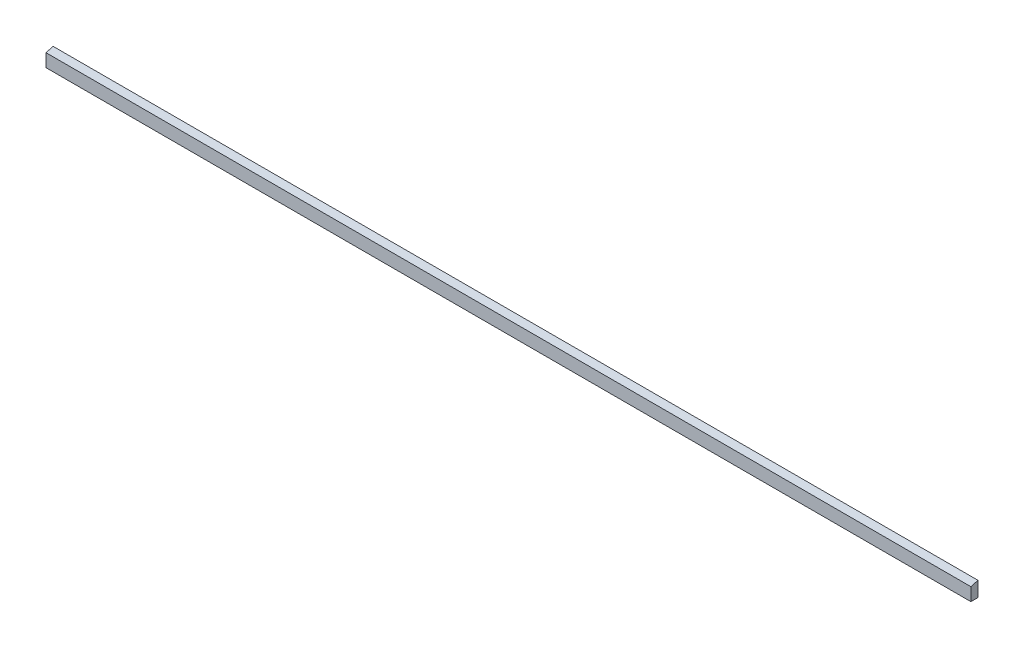
SolidWorks part; units mm, degrees
ref_plane "Front Plane" through (0, 0, 0) normal (0, 0, 1) x (1, 0, 0)
ref_plane "Top Plane" through (0, 0, 0) normal (0, 1, 0) x (1, 0, 0)
ref_plane "Right Plane" through (0, 0, 0) normal (1, 0, 0) x (0, 0, -1)
sketch "Sketch1" plane through (0, 0, 0) normal (1, 0, 0) x (0, 0, -1)
  line L0 (0, 0) -> (-18.2562, 0)
  line L1 (-18.2562, 0) -> (-18.2562, 33.2083)
  line L2 (-18.2562, 33.2083) -> (0, 38.1)
  line L3 (0, 38.1) -> (0, 0)
  dimension "D1" = 18.2562
  dimension "D2" = 38.1
  dimension "D3" = 75
extrude "Boss-Extrude1" add sketch "Sketch1" along normal blind 2362.2
